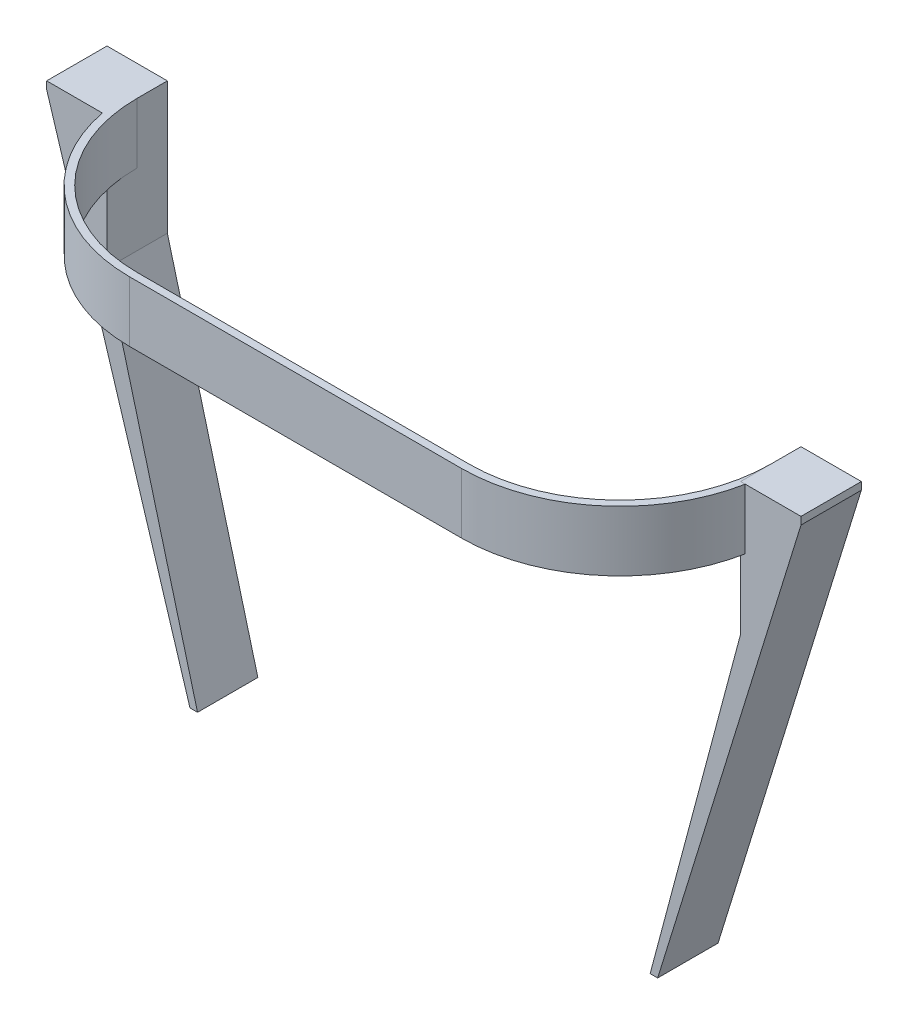
SolidWorks part; units mm, degrees
ref_plane "Front" through (0, 0, 0) normal (0, 0, 1) x (1, 0, 0)
ref_plane "Top" through (0, 0, 0) normal (0, 1, 0) x (1, 0, 0)
ref_plane "Right" through (0, 0, 0) normal (1, 0, 0) x (0, 0, -1)
sketch "草图12" plane through (0, 0, 0) normal (0, 0, 1) x (1, 0, 0)
  line L0 (-42.083, 0) -> (437.917, 0) construction
  line L1 (0, 0) -> (0, 73.6725) construction
  line L2 (-124, 0) -> (-120, 0)
  line L3 (-120, 0) -> (-120, 327.8565) construction
  line L4 (-239.7337, 250) -> (83.2848, 250) construction
  line L5 (-377.4287, 180) -> (204.3719, 180) construction
  line L6 (-168, 297.3856) -> (-168, -105.0236) construction
  line L8 (-168, 180) -> (-168, 250)
  line L9 (-168, 250) -> (-200, 250)
  line L10 (-200, 250) -> (-200, 246)
  line L11 (-200, 246) -> (-124, 0)
  line L12 (-120, 0) -> (-168, 180)
  line L13 (120, 0) -> (120, 327.8565) construction
  line L14 (120, 0) -> (168, 180)
  line L15 (200, 246) -> (124, 0)
  line L16 (200, 250) -> (200, 246)
  line L17 (168, 250) -> (200, 250)
  line L18 (168, 180) -> (168, 250)
  line L19 (124, 0) -> (120, 0)
  dimension "D1" = 4
  dimension "D2" = 120
  dimension "D3" = 250
  dimension "D4" = 180
  dimension "D5" = 48
  dimension "D6" = 4
  dimension "D7" = 32
extrude "凸台-拉伸3" add sketch "草图12" along normal blind 32
sketch "草图13" plane through (0, 250, 0) normal (0, 1, 0) x (1, 0, 0)
  line L0 (-168, -16) -> (168, -16) construction
  line L1 (-168, -32) -> (-168, 0) construction
  line L2 (168, -32) -> (168, 0) construction
  line L5 (-88, -16) -> (88, -16) construction
  line L10 (-88, -96) -> (88, -96)
  line L13 (-88, -16) -> (88, -16) construction
  line L15 (165.5193, -32) -> (168, -32) construction
  line L16 (-88, -100) -> (88, -100)
  line L17 (-172, -16) -> (-168, -16)
  line L18 (168, -16) -> (172, -16)
  arc A2 (-168, -16) -> (-88, -96) centre (-88, -16) ccw
  arc A3 (88, -96) -> (168, -16) centre (88, -16) ccw
  arc A4 (-172, -16) -> (-88, -100) centre (-88, -16) ccw
  arc A5 (88, -100) -> (172, -16) centre (88, -16) ccw
  point P11 (0, -16)
  point P17 (0, -16)
  point P18 (0, -16.5036)
  point P24 (0, -16.5036)
extrude "凸台-拉伸5" add sketch "草图13" against normal blind 32
